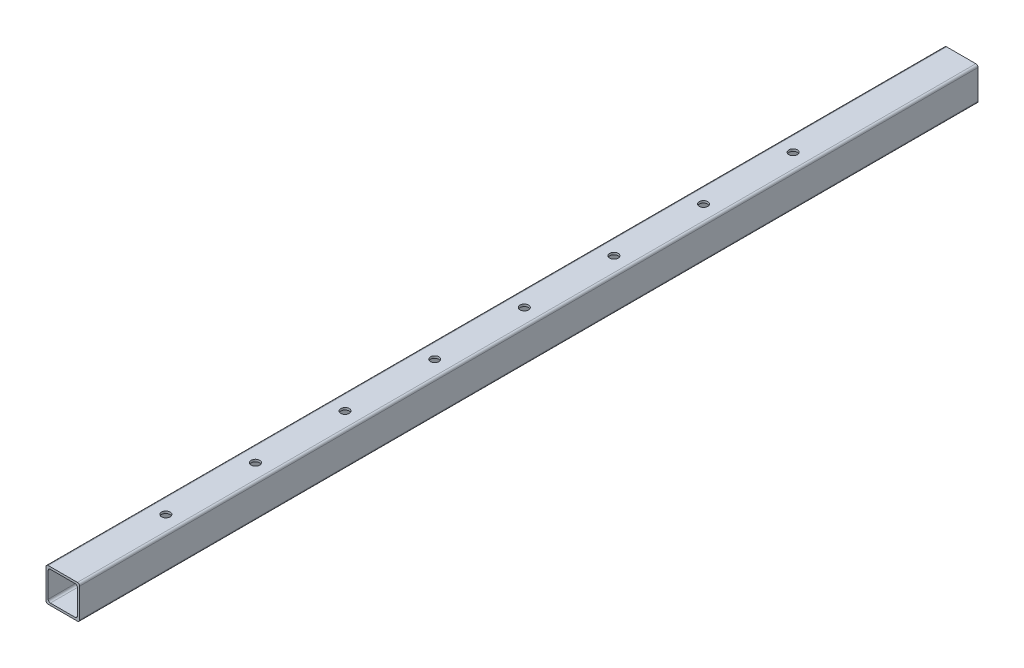
SolidWorks part; units mm, degrees
ref_plane "Front Plane" through (0, 0, 0) normal (0, 0, 1) x (1, 0, 0)
ref_plane "Top Plane" through (0, 0, 0) normal (0, 1, 0) x (1, 0, 0)
ref_plane "Right Plane" through (0, 0, 0) normal (1, 0, 0) x (0, 0, -1)
sketch "Sketch1" plane through (0, 0, 0) normal (0, 0, 1) x (1, 0, 0)
  line L0 (-9.525, 0) -> (9.525, 0) construction
  line L1 (0, -9.525) -> (0, 9.525) construction
  line L2 (8.2804, 0) -> (8.2804, 8.2804) construction
  line L3 (-9.525, -9.525) -> (9.525, -9.525) construction
  line L4 (-9.525, -9.525) -> (-9.525, 9.525) construction
  line L5 (-9.525, 9.525) -> (9.525, 9.525) construction
  line L6 (9.525, -9.525) -> (9.525, 9.525) construction
  line L7 (-9.525, -9.525) -> (9.525, 9.525) construction
  line L8 (-9.525, 9.525) -> (9.525, -9.525) construction
  line L9 (8.2804, 8.2804) -> (-8.2804, 8.2804) construction
  line L10 (-8.2804, 8.2804) -> (-8.2804, -8.2804) construction
  line L11 (-8.2804, -8.2804) -> (8.2804, -8.2804) construction
  line L12 (8.2804, -8.2804) -> (8.2804, 0) construction
  point P0 (0, 0)
  point P4 (0, 0)
  point P9 (0, 0)
  point P10 (8.2804, 0)
  point P13 (0, -8.2804)
  point P14 (-8.2804, 0)
  point P15 (0, 8.2804)
  dimension "Width" = 19.05
  dimension "Wall Thickness" = 1.2446
  dimension "Height" = 19.05
  dimension "D1" = 1.2446
  dimension "D2" = 1.2446
  dimension "D3" = 1.2446
sketch "Sketch2" plane through (0, 0, 0) normal (1, 0, 0) x (0, 0, -1)
  line L0 (254.635, 9.525) -> (-254.635, 9.525) construction
  point P3 (-232.7275, 9.525)
  point P5 (232.7275, 9.525)
  point P7 (0, 9.525)
  dimension "D1" = 21.9075
  dimension "D2" = 21.9075
  dimension "Length" = 509.27
sketch "Sketch3" plane through (0, 0, 0) normal (0, 0, 1) x (1, 0, 0)
  line L1 (9.525, 9.525) -> (-9.525, 9.525)
  line L2 (-9.525, 9.525) -> (-9.525, -9.525)
  line L3 (-9.525, -9.525) -> (9.525, -9.525) construction
  line L4 (-9.525, -9.525) -> (9.525, -9.525)
  line L5 (9.525, -9.525) -> (9.525, 9.525)
  line L6 (-8.2804, 8.2804) -> (8.2804, 8.2804)
  line L7 (8.2804, 8.2804) -> (8.2804, -8.2804)
  line L8 (8.2804, -8.2804) -> (-8.2804, -8.2804)
  line L9 (-8.2804, -8.2804) -> (-8.2804, 8.2804)
extrude "Boss-Extrude1" add sketch "Sketch3" along normal mid plane 509.27
fillet "Fillet1" radius 1.2446 8 edges at (-9.525, 9.525, 0) (8.2804, -8.2804, 0) (-8.2804, -8.2804, 0) (-8.2804, 8.2804, 0) (8.2804, 8.2804, 0) (9.525, -9.525, 0) (-9.525, -9.525, 0) (9.525, 9.525, 0)
sketch "Sketch4" plane through (0, 9.525, 0) normal (0, 1, 0) x (1, 0, 0)
  line L0 (0, 254.635) -> (0, 159.385) construction
  line L1 (8.2804, 254.635) -> (-8.2804, 254.635) construction
  line L2 (0, 159.385) -> (0, 108.585) construction
  circle A0 centre (0, 159.385) radius 2.413
  circle A1 centre (0, 108.585) radius 2.413
  circle A2 centre (0, 57.785) radius 2.413
  circle A3 centre (0, 6.985) radius 2.413
  circle A4 centre (0, -43.815) radius 2.413
  circle A5 centre (0, -94.615) radius 2.413
  circle A6 centre (0, -145.415) radius 2.413
  circle A7 centre (0, -196.215) radius 2.413
  dimension "D2" = 4.826
  dimension "D4" = 4.826
  dimension "D1" = 95.25
  dimension "D3" = 50.8
  dimension "D5" = 7
extrude "Cut-Extrude1" cut sketch "Sketch4" against normal up to next
sketch "Sketch6" plane through (-9.525, 0, 0) normal (-1, 0, 0) x (0, 0, 1)
  line L0 (-254.635, 0) -> (-179.705, 0) construction
  line L1 (-254.635, 8.2804) -> (-254.635, -8.2804) construction
  line L2 (-182.118, -1.651) -> (-187.198, -1.651)
  line L7 (-182.118, -6.477) -> (-177.292, -1.651) construction
  line L12 (-177.292, -6.477) -> (-182.118, -6.477)
  line L13 (-177.292, -6.477) -> (-177.292, -1.651)
  line L14 (-177.292, -1.651) -> (-182.118, -1.651)
  line L15 (-182.118, -6.477) -> (-182.118, -1.651) construction
  line L16 (-192.278, 9.525) -> (-192.278, -6.477)
  line L17 (-177.292, -6.477) -> (-182.118, -1.651) construction
  line L18 (-254.635, 9.525) -> (254.635, 9.525) construction
  line L19 (-192.278, -6.477) -> (-182.118, -6.477)
  line L20 (-187.198, -1.651) -> (-187.198, 9.525)
  line L21 (-187.198, 9.525) -> (-192.278, 9.525)
  point P12 (-179.705, -4.064)
  dimension "D1" = 74.93
  dimension "D2" = 16.002
  dimension "D3" = 4.826
  dimension "D4" = 4.826
  dimension "D5" = 10.16
  dimension "D6" = 5.08
extrude "Cut-Extrude3" [suppressed] cut sketch "Sketch6" against normal blind 6.35
pattern_linear "LPattern2" [suppressed] count 8 spacing 50.8
equation "\"D1@Boss-Extrude1\" = \"Length@Sketch2\""
equation "\"D1@Sketch2\" = \"Width@Sketch1\" * 1.15"
equation "\"D2@Sketch2\"=\"D1@Sketch2\""
equation "\"D1@Sketch1\"=\"Wall Thickness@Sketch1\""
equation "\"D2@Sketch1\"=\"Wall Thickness@Sketch1\""
equation "\"D3@Sketch1\"=\"Wall Thickness@Sketch1\""
equation "\"D1@Fillet1\"=\"Wall Thickness@Sketch1\""
